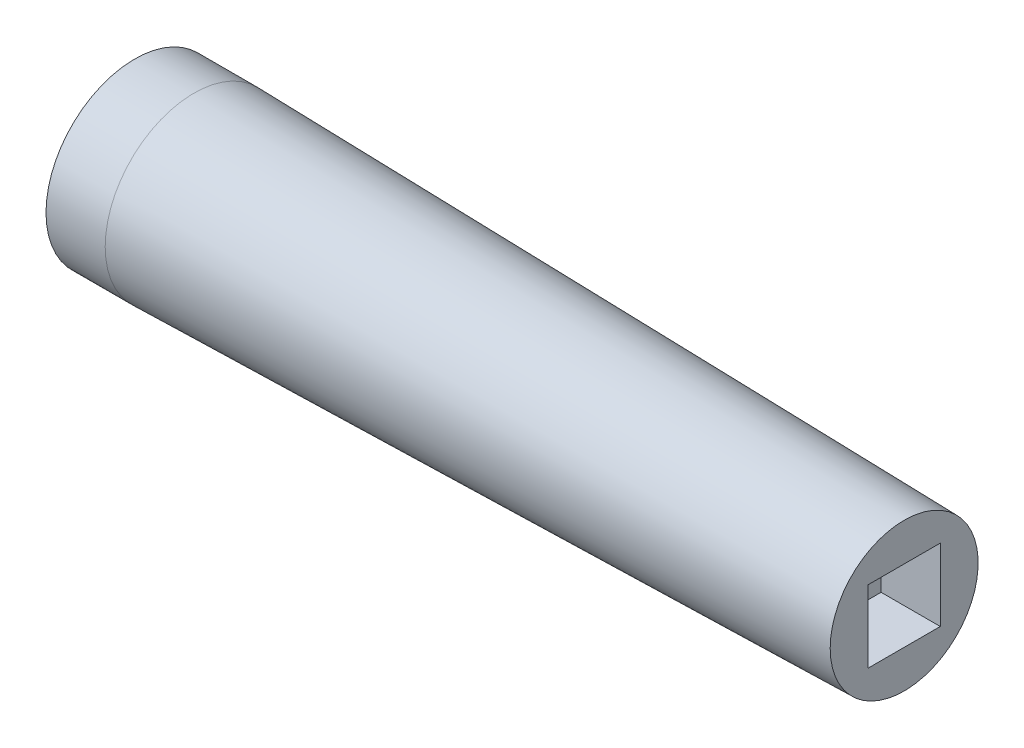
SolidWorks part; units mm, degrees
ref_plane "Front Plane" through (0, 0, 0) normal (0, 0, 1) x (1, 0, 0)
ref_plane "Top Plane" through (0, 0, 0) normal (0, 1, 0) x (1, 0, 0)
ref_plane "Right Plane" through (0, 0, 0) normal (1, 0, 0) x (0, 0, -1)
sketch "Sketch1" plane through (0, 0, 0) normal (0, 0, 1) x (1, 0, 0)
  line L0 (0, 0) -> (208.7573, 0) construction
  line L1 (0, 0) -> (165.1, 0)
  line L2 (165.1, 0) -> (165.1, 15.875)
  line L3 (165.1, 15.875) -> (12.7, 19.05)
  line L4 (12.7, 19.05) -> (0, 19.05)
  line L5 (0, 19.05) -> (0, 0)
  dimension "D1" = 165.1
  dimension "D2" = 12.7
  dimension "D3" = 38.1
  dimension "D4" = 31.75
revolve "Revolve2" add sketch "Sketch1" angle 360 about L0
sketch "Sketch3" plane through (165.1, 0, 0) normal (1, 0, 0) x (0, 0, -1)
  line L1 (-7.747, 7.747) -> (7.747, 7.747)
  line L2 (-7.747, 7.747) -> (-7.747, -7.747)
  line L3 (-7.747, -7.747) -> (7.747, -7.747)
  line L4 (7.747, 7.747) -> (7.747, -7.747)
  line L5 (-7.747, 7.747) -> (7.747, -7.747) construction
  line L6 (-7.747, -7.747) -> (7.747, 7.747) construction
  point P0 (0, 0)
  dimension "D1" = 15.494
  dimension "D2" = 15.494
extrude "Cut-Extrude1" cut sketch "Sketch3" against normal blind 12.7
